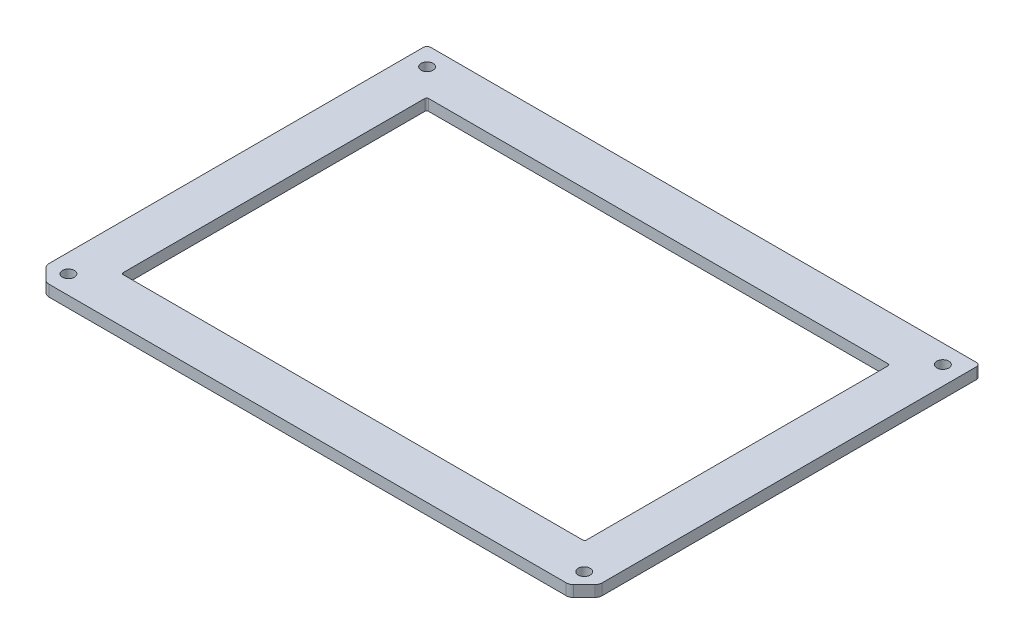
SolidWorks part; units mm, degrees
material "Acrylic (Medium-high impact)"
ref_plane "Front Plane" through (0, 0, 0) normal (0, 0, 1) x (1, 0, 0)
ref_plane "Top Plane" through (0, 0, 0) normal (0, 1, 0) x (1, 0, 0)
ref_plane "Right Plane" through (0, 0, 0) normal (1, 0, 0) x (0, 0, -1)
sketch "Sketch1" plane through (0, 0, 0) normal (0, 1, 0) x (1, 0, 0)
  line L0 (-74.1, 53.05) -> (74.1, 53.05)
  line L1 (-64.1, 43.05) -> (64.1, 43.05) construction
  line L2 (-64.1, 43.05) -> (-64.1, -43.05) construction
  line L3 (-64.1, -43.05) -> (64.1, -43.05) construction
  line L4 (64.1, 43.05) -> (64.1, -43.05) construction
  line L5 (-64.1, 43.05) -> (64.1, -43.05) construction
  line L6 (-64.1, -43.05) -> (64.1, 43.05) construction
  line L7 (74.1, 53.05) -> (74.1, -53.05)
  line L8 (-74.1, -53.05) -> (74.1, -53.05)
  line L9 (-74.1, 53.05) -> (-74.1, -53.05)
  line L10 (-64.1, 43.05) -> (-74.1, 53.05) construction
  line L11 (-62.05, 40.9) -> (62.05, 40.9)
  line L12 (-62.05, 40.9) -> (-62.05, -40.9)
  line L13 (-62.05, -40.9) -> (62.05, -40.9)
  line L14 (62.05, 40.9) -> (62.05, -40.9)
  line L15 (-62.05, 40.9) -> (62.05, -40.9) construction
  line L16 (-62.05, -40.9) -> (62.05, 40.9) construction
  line L17 (-74.1, 0) -> (74.1, 0) construction
  line L18 (0, 53.05) -> (0, -53.05) construction
  circle A0 centre (-69.1, 48.05) radius 1.6
  circle A1 centre (-69.1, -48.05) radius 1.6
  circle A2 centre (69.1, -48.05) radius 1.6
  circle A3 centre (69.1, 48.05) radius 1.6
  point P0 (0, 0)
  point P10 (0, 0)
  dimension "D6" = 3.2
  dimension "D1" = 128.2
  dimension "D2" = 86.1
  dimension "D4" = 81.8
  dimension "D5" = 124.1
  dimension "D3" = 10
extrude "Boss-Extrude1" add sketch "Sketch1" along normal blind 3
fillet "Fillet1" radius 1 4 edges at (74.1, 1.5, 53.05) (74.1, 1.5, -53.05) (-74.1, 1.5, -53.05) (-74.1, 1.5, 53.05)
fillet "Fillet2" radius 0.5 4 edges at (62.05, 1.5, 40.9) (62.05, 1.5, -40.9) (-62.05, 1.5, -40.9) (-62.05, 1.5, 40.9)
sketch "Sketch2" plane through (0, 3, 0) normal (0, 1, 0) x (-1, 0, 0)
  line L0 (77.1, 46.05) -> (67.1, 56.05)
  line L1 (67.1, 56.05) -> (77.1, 56.05)
  line L2 (77.1, 56.05) -> (77.1, 46.05)
  line L3 (74.1, -52.05) -> (74.1, 52.05) construction
  line L4 (73.1, 53.05) -> (-73.1, 53.05) construction
  line L5 (0, -53.05) -> (0, 53.05) construction
  line L6 (-73.1, -53.05) -> (73.1, -53.05) construction
  line L7 (-77.1, 56.05) -> (-77.1, 46.05)
  line L8 (-67.1, 56.05) -> (-77.1, 56.05)
  line L9 (-77.1, 46.05) -> (-67.1, 56.05)
  dimension "D1" = 10
  dimension "D2" = 45
  dimension "D3" = 3
  dimension "D4" = 3
extrude "Cut-Extrude1" cut sketch "Sketch2" against normal up to next
fillet "Fillet3" radius 2 4 edges at (74.1, 1.5, 49.05) (70.1, 1.5, 53.05) (-70.1, 1.5, 53.05) (-74.1, 1.5, 49.05)
